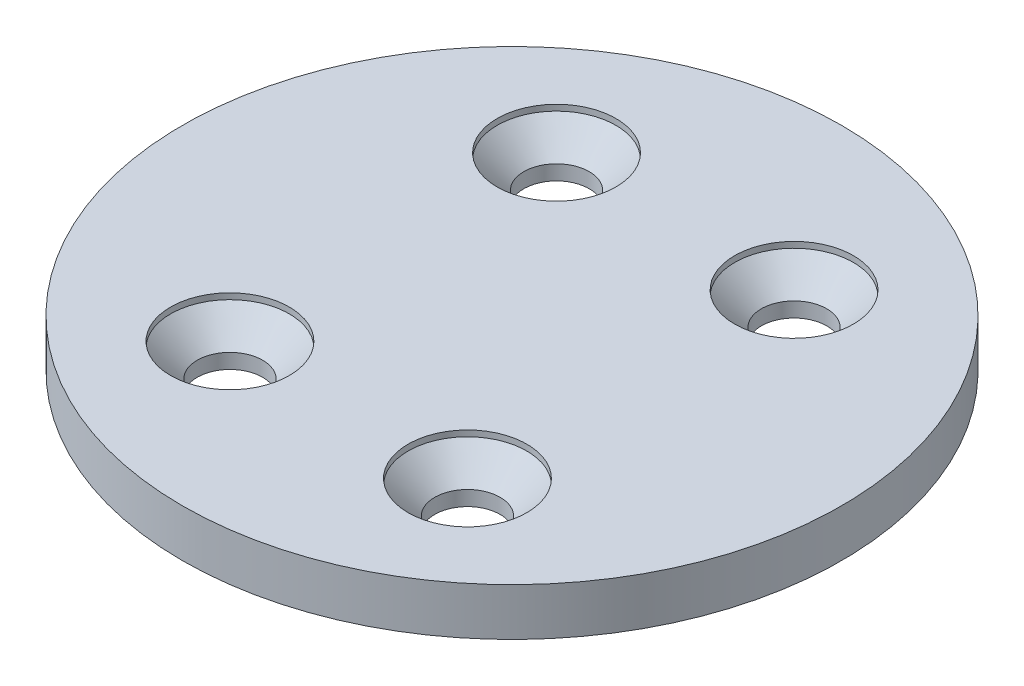
SolidWorks part; units mm, degrees
ref_plane "Front Plane" through (0, 0, 0) normal (0, 0, 1) x (1, 0, 0)
ref_plane "Top Plane" through (0, 0, 0) normal (0, 1, 0) x (1, 0, 0)
ref_plane "Right Plane" through (0, 0, 0) normal (1, 0, 0) x (0, 0, -1)
sketch "Sketch1" plane through (0, 0, 0) normal (0, 1, 0) x (1, 0, 0)
  line L0 (0, 0) -> (0, 68.5524) construction
  line L1 (0, 52.4907) -> (0, -49.3242) construction
  line L2 (10, -13.75) -> (10, 13.75)
  line L3 (10, -13.75) -> (-10, -13.75)
  line L4 (10, 13.75) -> (-10, 13.75)
  line L5 (-10, -13.75) -> (-10, 13.75)
  line L6 (10, -13.75) -> (-10, 13.75) construction
  line L7 (10, 13.75) -> (-10, -13.75) construction
  circle A0 centre (0, 0) radius 27.75
  circle A1 centre (-10, 13.75) radius 2.75
  circle A2 centre (10, 13.75) radius 2.75
  circle A3 centre (10, -13.75) radius 2.75
  circle A4 centre (-10, -13.75) radius 2.75
  dimension "D1" = 55.5
  dimension "D5" = 5.5
  dimension "D3" = 27.5
  dimension "D4" = 20
extrude "Boss-Extrude1" add sketch "Sketch1" along normal blind 4 contours A0 A4 L5 A1 L4 A2 L2 A3 L3 | A4 L3 A3 L2 A2 L4 A1 L5
hole_wizard "CSK for M5 Flat Head Machine Screw1" positions "Sketch18" profile "Sketch20" countersink size "M5" standard "ANSI Metric" end condition through all
sketch "Sketch18" plane through (0, 4, 0) normal (0, 1, 0) x (1, 0, 0)
  point P0 (10, 13.75)
  point P3 (10, -13.75)
  point P6 (-10, -13.75)
  point P9 (-10, 13.75)
sketch "Sketch20" plane through (10, 4, -13.75) normal (1, 0, 0) x (0, 0, 1)
  line L0 (0, 0) -> (0, 4)
  line L1 (0, 4) -> (2.75, 4)
  line L2 (2.75, 4) -> (2.75, 2.75)
  line L3 (2.75, 2.75) -> (5, 0.5)
  line L4 (5, 0.5) -> (5, 0)
  line L6 (5, 0) -> (0, 0)
  line L7 (-2.75, 2.75) -> (-5, 0.5) construction
  line L11 (0, -6.35) -> (0, 107.95) construction
  dimension "Thru Hole Dia." = 5.5
  dimension "Thru Hole Depth" = 4
  dimension "C'Sink Dia." = 10
  dimension "C'Sink Angle" = 90
  dimension "Head Clearance" = 0.5
sketch "Sketch3" plane through (0, 4, 4) normal (0, 1, 0) x (1, 0, 0)
  line L0 (-38.3333, -12.6667) -> (1.6667, -12.6667)
  line L1 (-38.3333, -12.6667) -> (-5, 20.6667)
  line L2 (-31.6667, -6) -> (8.3333, -6)
  line L3 (-25, 0.6667) -> (15, 0.6667)
  line L4 (-18.3333, 7.3333) -> (21.6667, 7.3333)
  line L5 (-11.6667, 14) -> (28.3333, 14)
  line L6 (-5, 20.6667) -> (35, 20.6667)
  line L7 (-28.3333, -12.6667) -> (5, 20.6667)
  line L8 (-18.3333, -12.6667) -> (15, 20.6667)
  line L9 (-8.3333, -12.6667) -> (25, 20.6667)
  line L10 (1.6667, -12.6667) -> (35, 20.6667)
  line L11 (15, 0.6667) -> (15, 7.3333)
  line L12 (-18.3333, 7.3333) -> (-18.3333, 0.6667)
  line L13 (15, 7.3333) -> (15, 14) construction
  line L14 (15, 14) -> (21.6667, 20.6667)
  line L15 (5, 14) -> (11.6667, 20.6667)
  line L16 (8.3333, 17.3333) -> (18.3333, 17.3333) construction
  line L17 (1.6667, 17.3333) -> (-8.3333, 17.3333) construction
  line L18 (-15, -6) -> (-21.6667, -12.6667)
  line L19 (-21.6667, 4) -> (18.3333, 4) construction
  line L20 (21.6667, 20.6667) -> (-21.6667, 20.6667) construction
  line L21 (0, 20.6667) -> (0, -8.2564) construction
  line L22 (0, 31.75) -> (0, -23.75) construction
  line L23 (-27.75, 4) -> (27.75, 4) construction
  circle A0 centre (0, 4) radius 27.75 construction
  dimension "D2" = 45
  dimension "D1" = 40
  dimension "D4" = 6.6667
  dimension "D3" = 6
  dimension "D5" = 5
sketch "Sketch21" plane through (0, 4, 0) normal (0, 1, 0) x (1, 0, 0)
  line L1 (27.75, 27.75) -> (-27.75, 27.75)
  line L2 (27.75, 27.75) -> (27.75, -27.75)
  line L3 (27.75, -27.75) -> (-27.75, -27.75)
  line L4 (-27.75, 27.75) -> (-27.75, -27.75)
  line L5 (27.75, 27.75) -> (-27.75, -27.75) construction
  line L6 (27.75, -27.75) -> (-27.75, 27.75) construction
  circle A0 centre (0, 0) radius 27.75 construction
  point P0 (0, 0)
  point P8 (0, 0)
equation "\"LOGO_SIZE\"= 40"
equation "\"SECTION_SIZE\"= \"LOGO_SIZE\" / 6"
equation "\"D1@Sketch3\"=\"LOGO_SIZE\""
equation "\"D4@Sketch3\"=\"SECTION_SIZE\""
